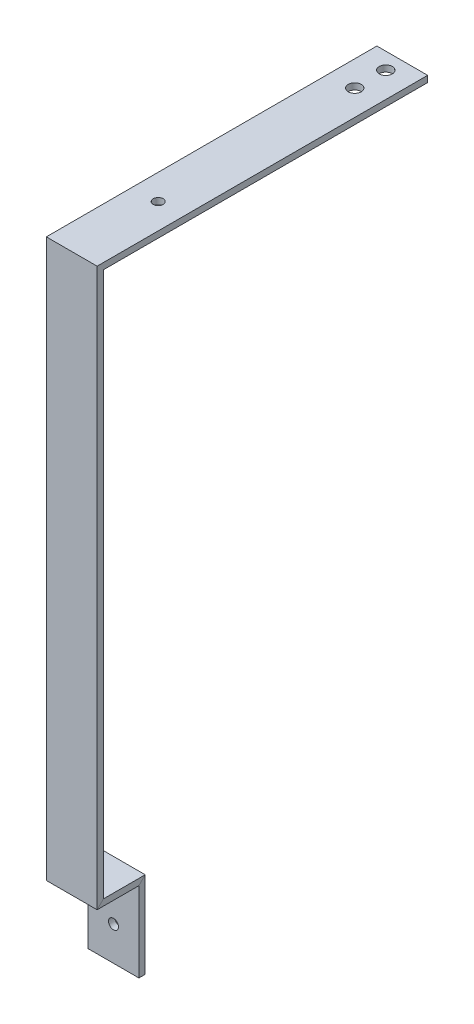
SolidWorks part; units mm, degrees
ref_plane "Alzado" through (0, 0, 0) normal (0, 0, 1) x (1, 0, 0)
ref_plane "Planta" through (0, 0, 0) normal (0, 1, 0) x (1, 0, 0)
ref_plane "Vista lateral" through (0, 0, 0) normal (1, 0, 0) x (0, 0, -1)
sketch "Croquis1" plane through (0, 0, 0) normal (0, 0, 1) x (1, 0, 0)
  line L1 (-25.4, 3.155) -> (25.4, 3.155)
  line L2 (-25.4, 3.155) -> (-25.4, -3.155)
  line L3 (-25.4, -3.155) -> (25.4, -3.155)
  line L4 (25.4, 3.155) -> (25.4, -3.155)
  line L5 (-25.4, 3.155) -> (25.4, -3.155) construction
  line L6 (-25.4, -3.155) -> (25.4, 3.155) construction
  point P0 (0, 0)
  dimension "D1" = 50.8
  dimension "D2" = 6.31
extrude "Saliente-Extruir1" add sketch "Croquis1" along normal blind 330.7
sketch "Croquis3" plane through (0, -3.155, 0) normal (0, -1, 0) x (1, 0, 0)
  line L1 (25.4, 324.39) -> (-25.4, 324.39)
  line L2 (25.4, 324.39) -> (25.4, 330.7)
  line L3 (25.4, 330.7) -> (-25.4, 330.7)
  line L4 (-25.4, 324.39) -> (-25.4, 330.7)
  line L5 (25.4, 324.39) -> (-25.4, 330.7) construction
  line L6 (25.4, 330.7) -> (-25.4, 324.39) construction
  point P0 (0, 327.545)
  dimension "D1" = 6.31
  dimension "D2" = 50.8
extrude "Saliente-Extruir2" add sketch "Croquis3" along normal blind 538.2
sketch "Croquis7" plane through (0, -541.355, 0) normal (0, -1, 0) x (1, 0, 0)
  line L0 (25.4, 324.39) -> (25.4, 330.7)
  line L1 (25.4, 330.7) -> (-25.4, 330.7)
  line L2 (-25.4, 330.7) -> (-25.4, 324.39)
  line L3 (-25.4, 324.39) -> (25.4, 324.39)
  line L4 (0, 324.39) -> (0, 330.7) construction
  line L5 (0, 330.7) -> (0, 327.545) construction
  line L6 (0, 327.545) -> (-7.9034, 327.545) construction
sketch3d "Croquis3D1"
  line L0 (0, -541.355, 327.545) -> (0, -551.355, 327.545)
  line L1 (0, -551.355, 327.545) -> (0, -551.355, 285.735)
  line L2 (0, -551.355, 285.735) -> (0, -634.515, 285.735)
  dimension "D1" = 10
  dimension "D2" = 41.81
  dimension "D3" = 83.16
sweep "Barrer1" add profiles "Croquis7" path "Croquis3D1"
sketch "Croquis8" plane through (0, 0, 282.58) normal (0, 0, -1) x (-1, 0, 0)
  line L0 (-2.7547, -689.1653) -> (0, -600.505) construction
  line L1 (0, -600.505) -> (4.75, -600.505) construction
  line L2 (0, -600.505) -> (0, -634.515) construction
  line L3 (25.4, -634.515) -> (-25.4, -634.515) construction
  circle A0 centre (0, -600.505) radius 5
  dimension "D1" = 10
  dimension "D2" = 34.01
extrude "Cortar-Extruir2" cut sketch "Croquis8" against normal blind 15.875
sketch "Croquis9" plane through (0, 3.155, 0) normal (0, 1, 0) x (1, 0, 0)
  line L0 (0, 0) -> (0, -16.5) construction
  line L1 (0, -16.5) -> (0, -47.5) construction
  circle A0 centre (0, -47.5) radius 6.5
  circle A1 centre (0, -16.5) radius 6.5
  dimension "D1" = 13
  dimension "D2" = 13
extrude "Cortar-Extruir3" cut sketch "Croquis9" against normal blind 15.875
sketch "Croquis11" plane through (0, 3.155, 0) normal (0, 1, 0) x (1, 0, 0)
  line L0 (0, -330.7) -> (0, -244.19) construction
  line L1 (25.4, -330.7) -> (-25.4, -330.7) construction
  circle A0 centre (0, -244.19) radius 5
  dimension "D2" = 10
  dimension "D1" = 86.51
extrude "Cortar-Extruir5" cut sketch "Croquis11" against normal blind 10
